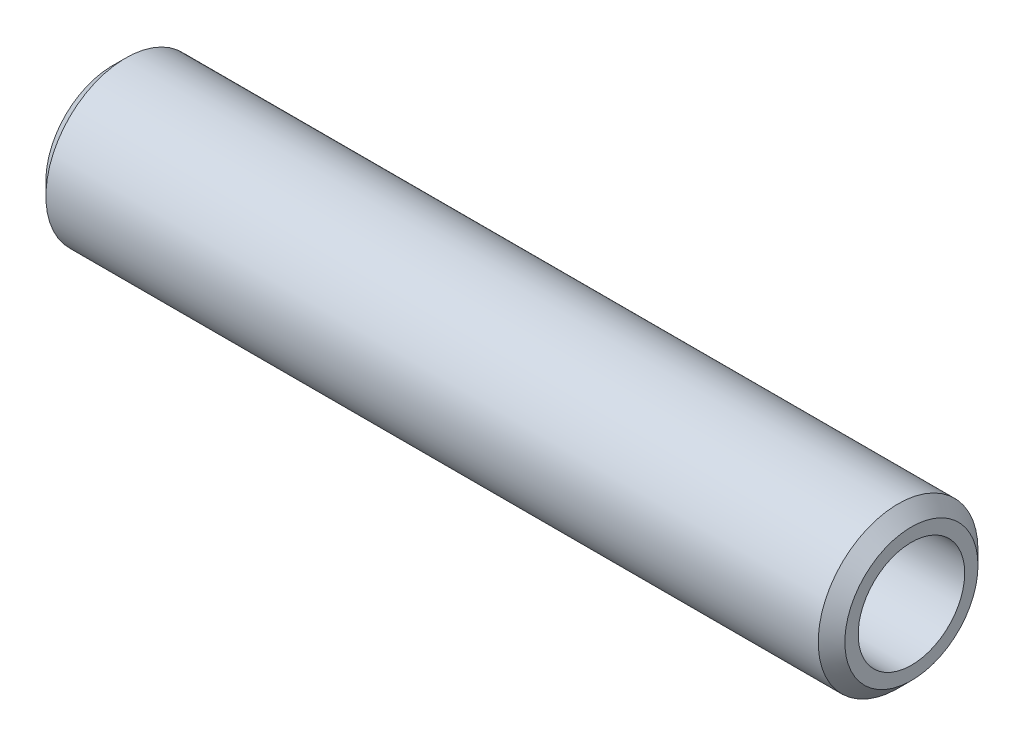
SolidWorks part; units mm, degrees
material "AISI 304"
ref_plane "Plan de face" through (0, 0, 0) normal (0, 0, 1) x (1, 0, 0)
ref_plane "Plan de dessus" through (0, 0, 0) normal (0, 1, 0) x (1, 0, 0)
ref_plane "Plan de droite" through (0, 0, 0) normal (1, 0, 0) x (0, 0, -1)
sketch "Esquisse1" plane through (0, 0, 0) normal (1, 0, 0) x (0, 0, -1)
  circle A0 centre (0, 0) radius 2
  circle A1 centre (0, 0) radius 3
  dimension "D1" = 6
  dimension "D2" = 4
extrude "Boss.-Extru.1" add sketch "Esquisse1" along normal mid plane 30
chamfer "Chanfrein1" distance 0.5 angle 45 2 edges at (-15, 0, -3) (15, 0, -3)
